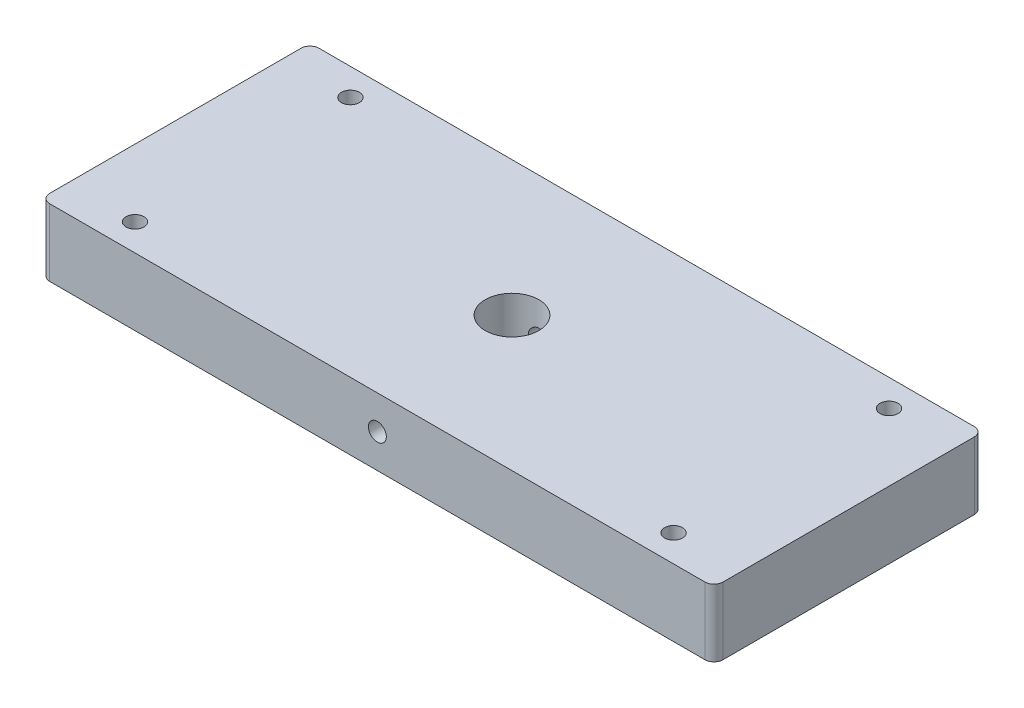
SolidWorks part; units mm, degrees
material "Cedar"
ref_plane "Plan de face" through (0, 0, 0) normal (0, 0, 1) x (1, 0, 0)
ref_plane "Plan de dessus" through (0, 0, 0) normal (0, 1, 0) x (1, 0, 0)
ref_plane "Plan de droite" through (0, 0, 0) normal (1, 0, 0) x (0, 0, -1)
sketch "Sketch1" plane through (0, 0, 0) normal (0, 1, 0) x (1, 0, 0)
  line L1 (-73, 30) -> (73, 30)
  line L2 (-75, 28) -> (-75, -28)
  line L3 (-73, -30) -> (73, -30)
  line L4 (75, 28) -> (75, -28)
  line L5 (-75, 30) -> (75, -30) construction
  line L6 (-75, -30) -> (75, 30) construction
  arc A0 (73, 30) -> (75, 28) centre (73, 28) cw
  arc A1 (73, -30) -> (75, -28) centre (73, -28) ccw
  arc A2 (-75, -28) -> (-73, -30) centre (-73, -28) ccw
  arc A3 (-73, 30) -> (-75, 28) centre (-73, 28) ccw
  circle A4 centre (0, 0) radius 5.975
  circle A5 centre (-60, 24) radius 2
  circle A6 centre (-60, -24) radius 2
  circle A7 centre (60, -24) radius 2
  circle A8 centre (60, 24) radius 2
  point P0 (0, 0)
  point P28 (0, 0)
  point P29 (0, 0)
  point P30 (0, 0)
  point P31 (0, 0)
  dimension "D3" = 2
  dimension "D4" = 11.95
  dimension "D6" = 4
  dimension "D1" = 150
  dimension "D2" = 60
  dimension "D5" = 6
extrude "Boss-Extrude1" add sketch "Sketch1" along normal mid plane 15
sketch "Sketch2" plane through (0, 0, 30) normal (0, 0, 1) x (1, 0, 0)
  circle A0 centre (0, 0) radius 2
  dimension "D1" = 4
extrude "Cut-Extrude1" cut sketch "Sketch2" against normal through all
